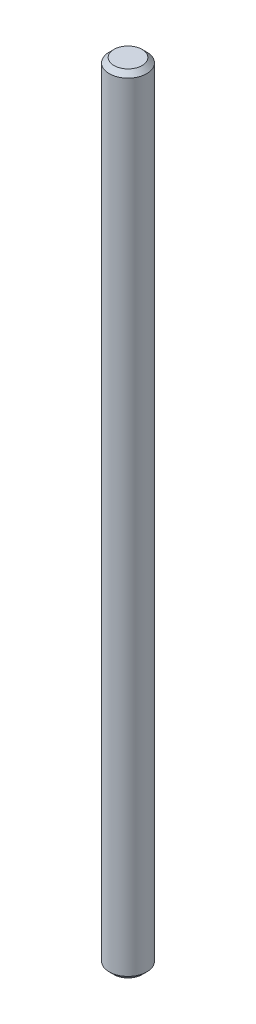
SolidWorks part; units mm, degrees
material "AISI 4340 Steel, annealed"
ref_plane "Front Plane" through (0, 0, 0) normal (0, 0, 1) x (1, 0, 0)
ref_plane "Top Plane" through (0, 0, 0) normal (0, 1, 0) x (1, 0, 0)
ref_plane "Right Plane" through (0, 0, 0) normal (1, 0, 0) x (0, 0, -1)
sketch "Sketch1" plane through (0, 0, 0) normal (0, 1, 0) x (1, 0, 0)
  circle A0 centre (0, 0) radius 2
  dimension "D1" = 4
extrude "Boss-Extrude1" add sketch "Sketch1" along normal mid plane 84
chamfer "Chamfer1" distance 0.5 angle 45 2 edges at (0, 42, 2) (0, -42, 2)
cosmetic thread "Cosmetic Thread1" parameters "D1"=8, "D2"=3.22
cosmetic thread "Cosmetic Thread2" parameters "D1"=12, "D2"=3.22
